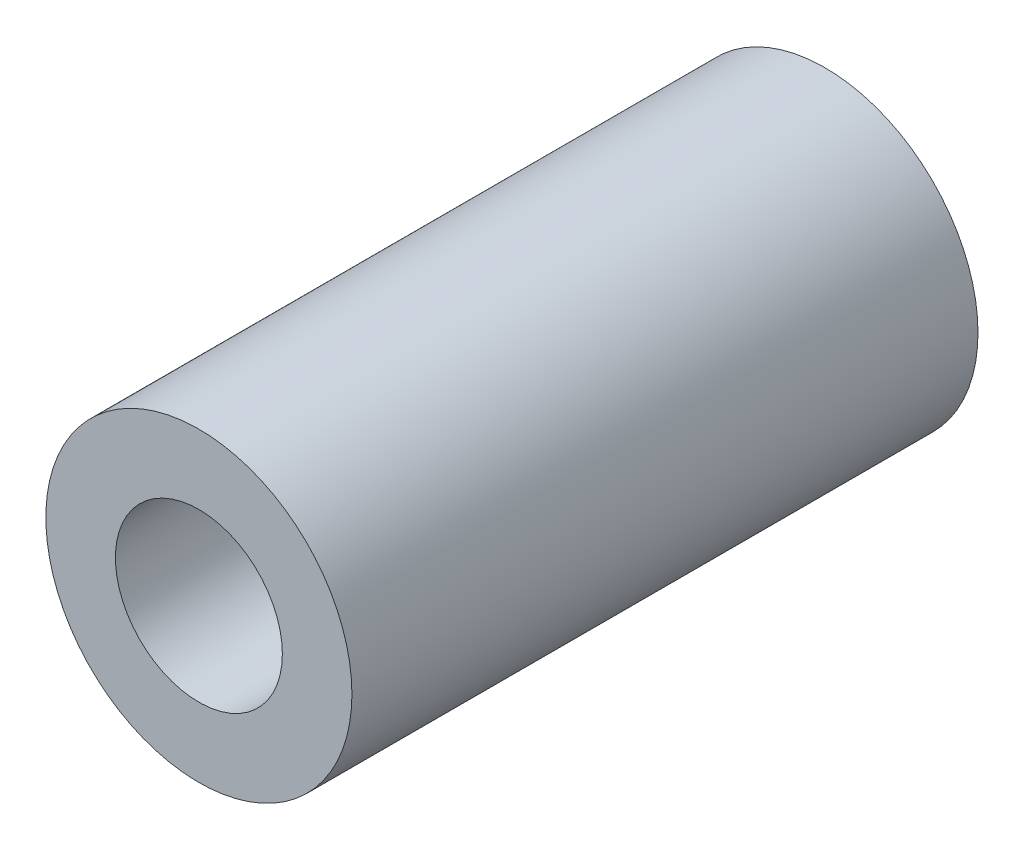
SolidWorks part; units mm, degrees
ref_plane "Спереди" through (0, 0, 0) normal (0, 0, 1) x (1, 0, 0)
ref_plane "Сверху" through (0, 0, 0) normal (0, 1, 0) x (1, 0, 0)
ref_plane "Справа" through (0, 0, 0) normal (1, 0, 0) x (0, 0, -1)
sketch "Эскиз1" plane through (0, 0, 0) normal (0, 0, 1) x (1, 0, 0)
  circle A0 centre (0, 0) radius 1.2
  circle A1 centre (0, 0) radius 2.2
  dimension "D1" = 2.4
  dimension "D2" = 4.4
extrude "Бобышка-Вытянуть1" add sketch "Эскиз1" along normal blind 9
